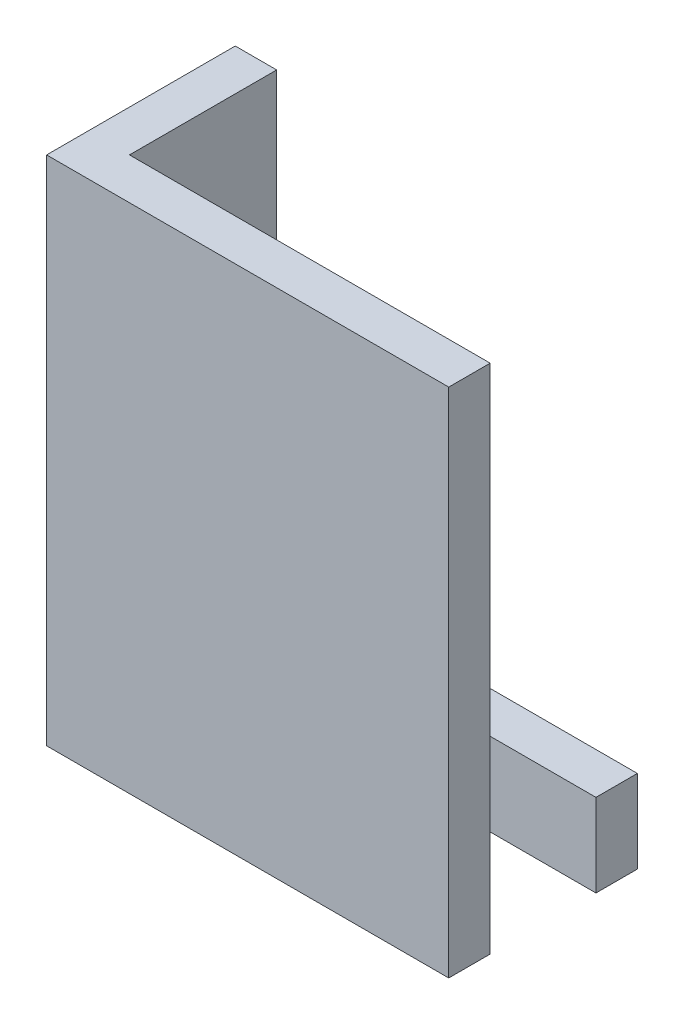
SolidWorks part; units mm, degrees
ref_plane "Front Plane" through (0, 0, 0) normal (0, 0, 1) x (1, 0, 0)
ref_plane "Top Plane" through (0, 0, 0) normal (0, 1, 0) x (1, 0, 0)
ref_plane "Right Plane" through (0, 0, 0) normal (1, 0, 0) x (0, 0, -1)
sketch "Sketch1" plane through (0, 0, 0) normal (0, 1, 0) x (1, 0, 0)
  line L2 (-2.7551, -8.5885) -> (-2.7551, -22.2485)
  line L3 (-2.7551, -22.2485) -> (26.3649, -22.2485)
  line L6 (0.2449, -8.5885) -> (0.2449, -19.2485)
  line L7 (0.2449, -19.2485) -> (26.3649, -19.2485)
  line L9 (26.3649, -19.2485) -> (26.3649, -22.2485)
  line L10 (-2.7551, -8.5885) -> (0.2449, -8.5885)
  dimension "D2" = 10.66
  dimension "D3" = 3
  dimension "D4" = 26.12
  dimension "D6" = 3
extrude "Boss-Extrude1" add sketch "Sketch1" along normal blind 37.06
sketch "Sketch2" plane through (0, 0, 0) normal (0, 1, 0) x (1, 0, 0)
  line L0 (0.2449, -11.5885) -> (26.3649, -11.5885)
  line L1 (0.2449, -19.2485) -> (0.2449, -8.5885) construction
  line L2 (26.3649, -11.5885) -> (26.3649, -8.5885)
  line L3 (26.3649, -8.5885) -> (0.2449, -8.5885)
  line L4 (0.2449, -8.5885) -> (0.2449, -11.5885)
  line L5 (26.3649, -19.2485) -> (0.2449, -19.2485) construction
  dimension "D1" = 3
  dimension "D2" = 7.66
  dimension "D3" = 26.12
extrude "Boss-Extrude2" add sketch "Sketch2" along normal blind 6
